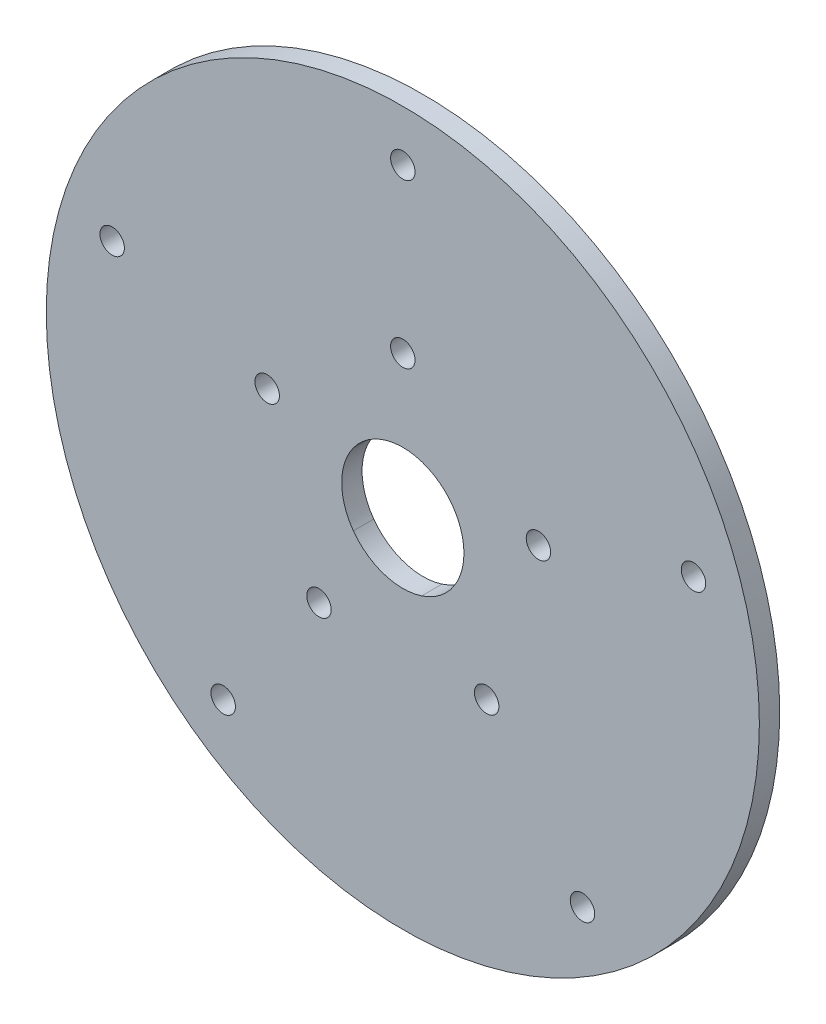
SolidWorks part; units mm, degrees
material "ASTM A36 Steel"
ref_plane "Front Plane" through (0, 0, 0) normal (0, 0, 1) x (1, 0, 0)
ref_plane "Top Plane" through (0, 0, 0) normal (0, 1, 0) x (1, 0, 0)
ref_plane "Right Plane" through (0, 0, 0) normal (1, 0, 0) x (0, 0, -1)
sketch "Sketch1" plane through (0, 0, 0) normal (0, 0, 1) x (1, 0, 0)
  circle A0 centre (0, 0) radius 175
  circle A1 centre (0, 0) radius 30
  circle A2 centre (-0.0007, 0.001) radius 30
  circle A8 centre (0, 0.0019) radius 30
  circle A11 centre (0.0011, 0.0015) radius 30
  circle A14 centre (0.0011, 0.0004) radius 30
  point P37 (0.0003, 0.001)
  dimension "D1" = 350
  dimension "D2" = 60
  dimension "D6" = 5
extrude "Boss-Extrude2" add sketch "Sketch1" along normal blind 10
sketch "Sketch2" plane through (0, 0, 0) normal (0, 0, -1) x (-1, 0, 0)
  circle A0 centre (0, 70) radius 6
  circle A1 centre (0, 150) radius 6
  dimension "D1" = 12
  dimension "D2" = 12
  dimension "D3" = 70
  dimension "D4" = 80
extrude "Cut-Extrude1" cut sketch "Sketch2" against normal through all
pattern_circular "CirPattern2" count 5 over 360 about axis through (0, 0, 0) along (0, 0, 1) of "Cut-Extrude1"
